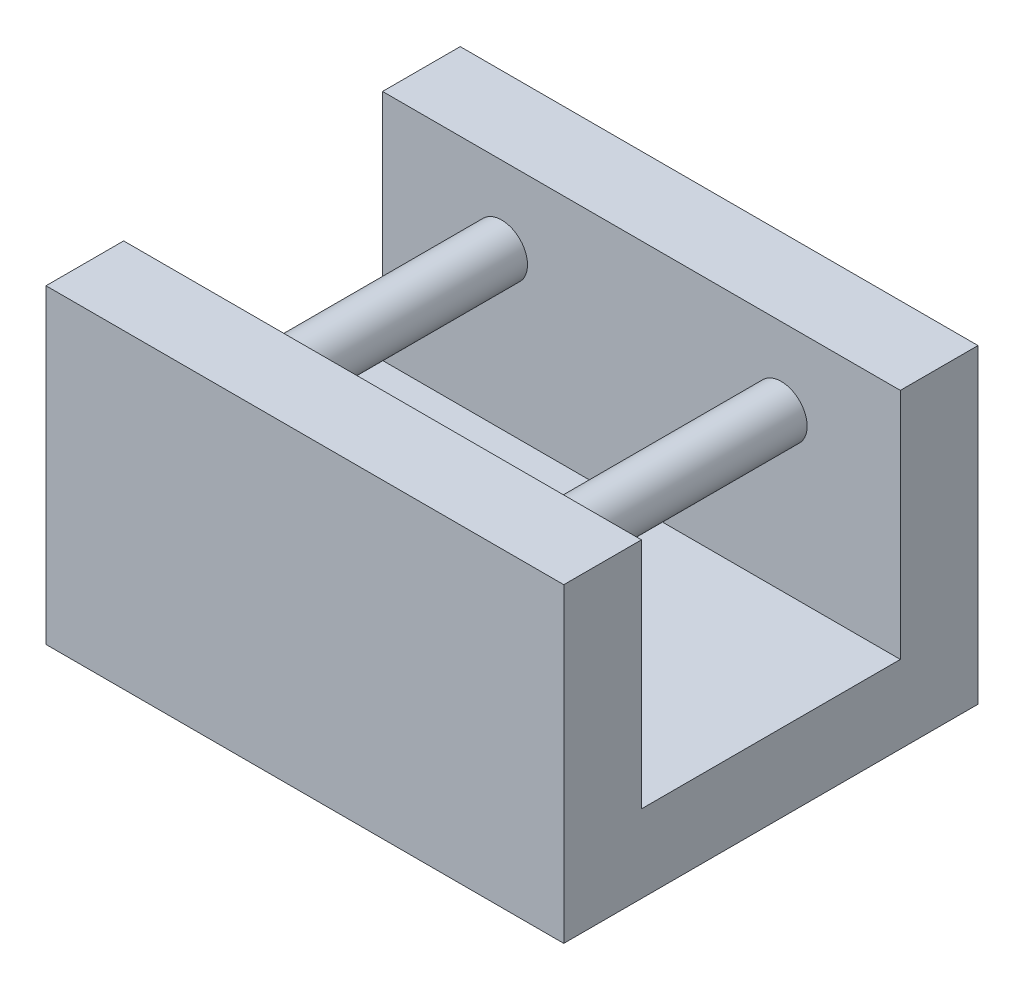
SolidWorks part; units mm, degrees
ref_plane "Front Plane" through (0, 0, 0) normal (0, 0, 1) x (1, 0, 0)
ref_plane "Top Plane" through (0, 0, 0) normal (0, 1, 0) x (1, 0, 0)
ref_plane "Right Plane" through (0, 0, 0) normal (1, 0, 0) x (0, 0, -1)
sketch "Sketch1" plane through (0, 0, 0) normal (1, 0, 0) x (0, 0, -1)
  line L0 (0, 0) -> (0, 60)
  line L1 (0, 60) -> (15, 60)
  line L2 (15, 60) -> (15, 15)
  line L3 (15, 15) -> (65, 15)
  line L4 (65, 15) -> (65, 60)
  line L5 (65, 60) -> (80, 60)
  line L6 (80, 60) -> (80, 0)
  line L7 (80, 0) -> (0, 0)
  line L8 (15, 15) -> (15, 0) construction
  dimension "D1" = 50
  dimension "D2" = 60
  dimension "D3" = 15
extrude "Boss-Extrude1" add sketch "Sketch1" along normal blind 100
sketch "Sketch2" plane through (0, 0, -15) normal (0, 0, -1) x (-1, 0, 0)
  line L0 (-100, 15) -> (0, 15) construction
  line L1 (-77, 45) -> (-23, 45) construction
  line L2 (-100, 60) -> (0, 60) construction
  circle A0 centre (-77, 45) radius 5
  circle A1 centre (-23, 45) radius 5
  point P6 (-50, 45)
  point P9 (-50, 60)
  dimension "D2" = 10
  dimension "D1" = 30
  dimension "D3" = 54
extrude "Boss-Extrude2" add sketch "Sketch2" along normal up to surface (50 mm away) up to face at (50, 37.5, -65)
